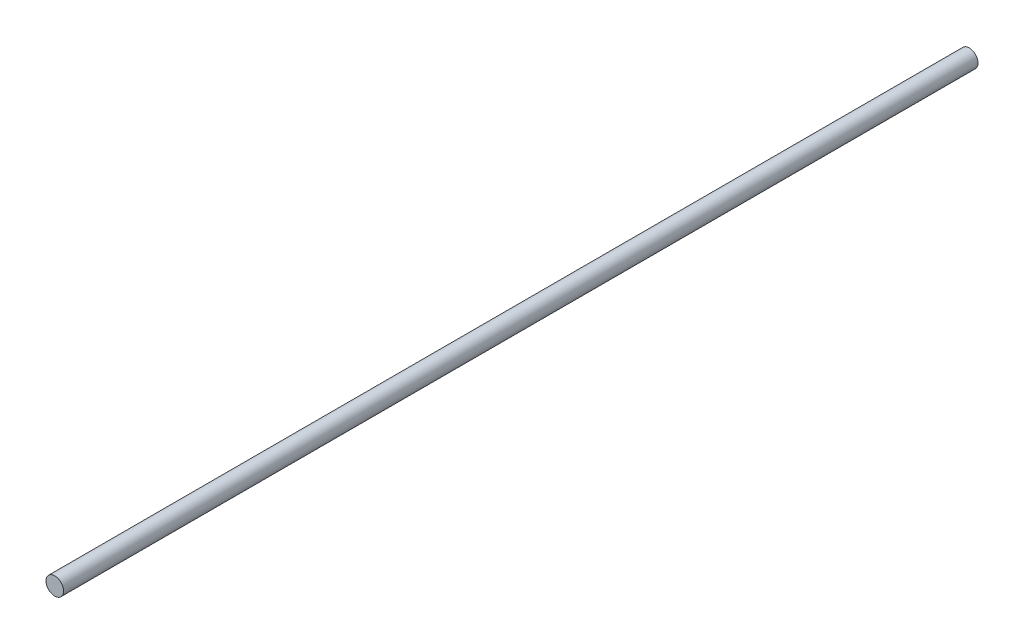
SolidWorks part; units mm, degrees
ref_plane "Front Plane" through (0, 0, 0) normal (0, 0, 1) x (1, 0, 0)
ref_plane "Top Plane" through (0, 0, 0) normal (0, 1, 0) x (1, 0, 0)
ref_plane "Right Plane" through (0, 0, 0) normal (1, 0, 0) x (0, 0, -1)
sketch "Sketch1" plane through (0, 0, 0) normal (0, 0, 1) x (1, 0, 0)
  circle A0 centre (0, 0) radius 5.5562
  dimension "D1" = 11.1125
extrude "Boss-Extrude1" add sketch "Sketch1" along normal mid plane 577.85
sketch "Sketch2" plane through (0, 0, 288.925) normal (0, 0, 1) x (1, 0, 0)
  line L0 (0, 5.5562) -> (0, -5.5562) construction
  circle A0 centre (0, 0) radius 5.5562 construction
sketch "Sketch3" plane through (0, 0, -288.925) normal (0, 0, -1) x (-1, 0, 0)
  line L0 (0, 5.5562) -> (0, -5.5562) construction
  circle A0 centre (0, 0) radius 5.5562 construction
ref_plane "Plane1" through (0, 0, 0) normal (-1, 0, 0) x (0, -1, 0)
